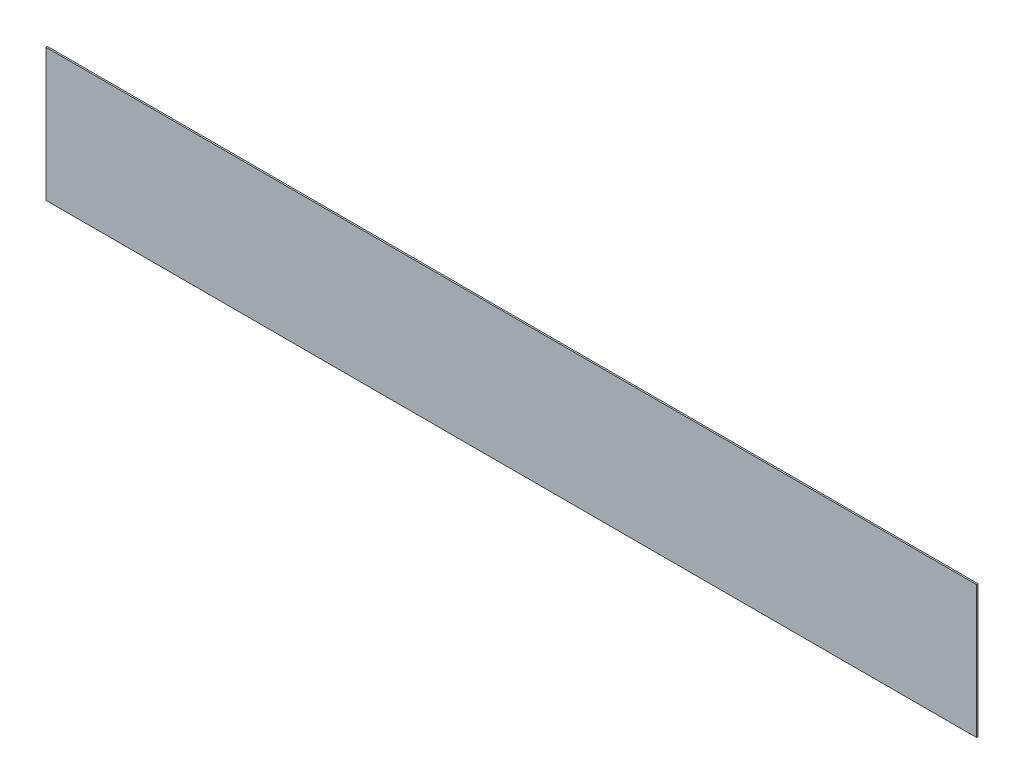
SolidWorks part; units mm, degrees
ref_plane "Front Plane" through (0, 0, 0) normal (0, 0, 1) x (1, 0, 0)
ref_plane "Top Plane" through (0, 0, 0) normal (0, 1, 0) x (1, 0, 0)
ref_plane "Right Plane" through (0, 0, 0) normal (1, 0, 0) x (0, 0, -1)
other "Configuration Table"
sketch "Sketch1" plane through (0, 0, 0) normal (0, 0, 1) x (1, 0, 0)
  line L1 (0, 0) -> (618, 0)
  line L2 (0, 0) -> (0, 88)
  line L3 (0, 88) -> (618, 88)
  line L4 (618, 0) -> (618, 88)
extrude "CEK_donmus_on_ic_sac_1.0_1" add sketch "Sketch1" along normal blind 1 separate body
